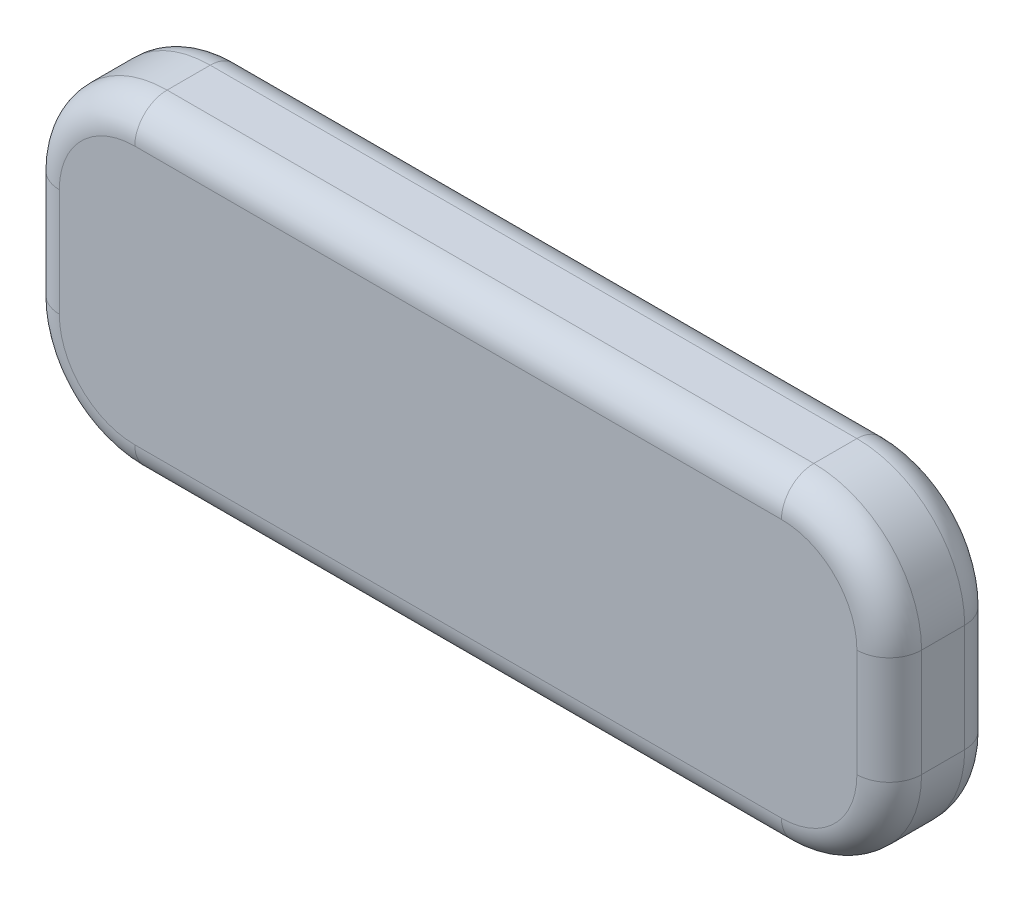
SolidWorks part; units mm, degrees
ref_plane "前视基准面" through (0, 0, 0) normal (0, 0, 1) x (1, 0, 0)
ref_plane "上视基准面" through (0, 0, 0) normal (0, 1, 0) x (1, 0, 0)
ref_plane "右视基准面" through (0, 0, 0) normal (1, 0, 0) x (0, 0, -1)
other "Configuration Table"
sketch "草图1" plane through (0, 0, 0) normal (0, 0, 1) x (1, 0, 0)
  line L1 (40, -15) -> (-40, -15)
  line L2 (40, -15) -> (40, 15)
  line L3 (40, 15) -> (-40, 15)
  line L4 (-40, -15) -> (-40, 15)
  line L5 (40, -15) -> (-40, 15) construction
  line L6 (40, 15) -> (-40, -15) construction
  point P0 (0, 0)
  dimension "D1" = 80
  dimension "D2" = 30
extrude "凸台-拉伸1" add sketch "草图1" along normal blind 10
fillet "圆角1" radius 10 4 edges at (40, -15, 5) (40, 15, 5) (-40, 15, 5) (-40, -15, 5)
fillet "圆角3" radius 3 16 edges at (-37.0711, -12.0711, 0) (-40, 0, 0) (-37.0711, 12.0711, 0) (37.0711, 12.0711, 0) (40, 0, 0) (37.0711, -12.0711, 0) (37.0711, 12.0711, 10) (40, 0, 10) (37.0711, -12.0711, 10) (-37.0711, -12.0711, 10) (-40, 0, 10) (-37.0711, 12.0711, 10) (0, 15, 0) (0, -15, 0) (0, -15, 10) (0, 15, 10)
